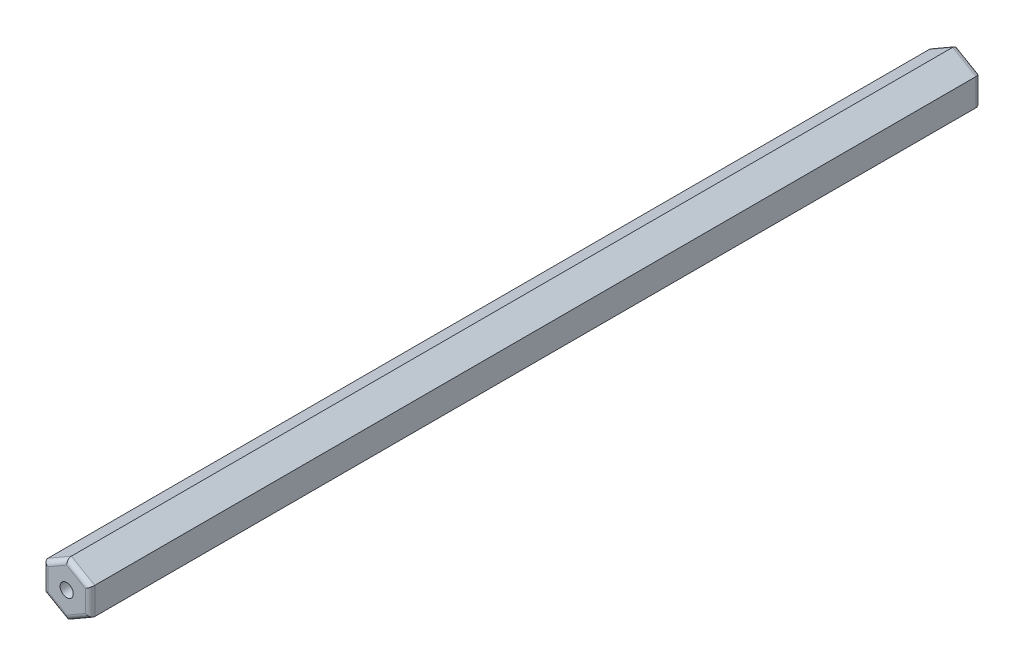
SolidWorks part; units mm, degrees
material "Inox rev"
ref_plane "Plano frontal" through (0, 0, 0) normal (0, 0, 1) x (1, 0, 0)
ref_plane "Plano superior" through (0, 0, 0) normal (0, 1, 0) x (1, 0, 0)
ref_plane "Plano direito" through (0, 0, 0) normal (1, 0, 0) x (0, 0, -1)
ref_plane "Plano1" through (0, 0, 135) normal (0, 0, 1) x (1, 0, 0)
sketch "Esboço1" plane through (0, 0, 135) normal (0, 0, 1) x (1, 0, 0)
  line L0 (-55.0021, 2.8868) -> (-57.5021, 1.4434)
  line L1 (-57.5021, 1.4434) -> (-57.5021, -1.4434)
  line L2 (-57.5021, -1.4434) -> (-55.0021, -2.8868)
  line L3 (-55.0021, -2.8868) -> (-52.5021, -1.4434)
  line L4 (-52.5021, -1.4434) -> (-52.5021, 1.4434)
  line L5 (-52.5021, 1.4434) -> (-55.0021, 2.8868)
  line L6 (-55.0021, 2.8868) -> (-55.0021, -2.8868) construction
  circle A0 centre (-55.0021, 0) radius 2.8868 construction
  dimension "D1" = 5
extrude "Ressalto-extrusão1" add sketch "Esboço1" against normal blind 95
fillet "Filete1" radius 0.5 12 edges at (-53.7521, -2.1651, 135) (-56.2521, -2.1651, 135) (-52.5021, 0, 135) (-57.5021, 0, 135) (-53.7521, 2.1651, 135) (-56.2521, 2.1651, 135) (-53.7521, -2.1651, 40) (-56.2521, -2.1651, 40) (-52.5021, 0, 40) (-57.5021, 0, 40) (-53.7521, 2.1651, 40) (-56.2521, 2.1651, 40)
sketch "Esboço2" plane through (0, 0, 135) normal (0, 0, 1) x (1, 0, 0)
  line L0 (-53.0021, -1.1547) -> (-53.0021, 1.1547) construction
  circle A0 centre (-55.0021, 0) radius 0.7015
  point P2 (-53.0021, 0)
extrude "Corte-extrusão1" cut sketch "Esboço2" against normal through all
